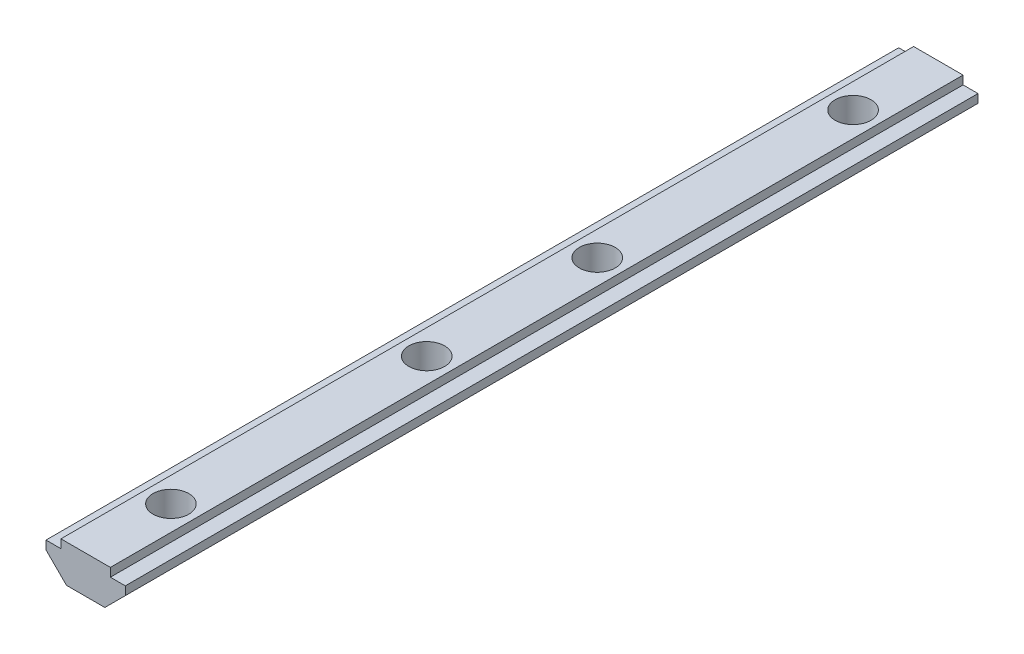
SolidWorks part; units mm, degrees
ref_plane "Front Plane" through (0, 0, 0) normal (0, 0, 1) x (1, 0, 0)
ref_plane "Top Plane" through (0, 0, 0) normal (0, 1, 0) x (1, 0, 0)
ref_plane "Right Plane" through (0, 0, 0) normal (1, 0, 0) x (0, 0, -1)
sketch "Sketch1" plane through (0, 0, 0) normal (0, 0, 1) x (1, 0, 0)
  line L0 (2.25, 0) -> (-2.25, 0)
  line L1 (-2.25, 0) -> (-4.65, 2.4)
  line L2 (-4.65, 2.4) -> (-4.65, 3.4)
  line L3 (-4.65, 3.4) -> (-2.9, 3.4)
  line L4 (-2.9, 3.4) -> (-2.9, 4.4)
  line L5 (-2.9, 4.4) -> (2.9, 4.4)
  line L6 (0, 4.4) -> (0, 0) construction
  line L7 (2.9, 3.4) -> (2.9, 4.4)
  line L8 (4.65, 3.4) -> (2.9, 3.4)
  line L9 (4.65, 2.4) -> (4.65, 3.4)
  line L10 (2.25, 0) -> (4.65, 2.4)
  point P3 (-2.2247, 0)
  dimension "D1" = 5.8
  dimension "D2" = 4.4
  dimension "D3" = 1
  dimension "D4" = 9.3
  dimension "D5" = 45
  dimension "D6" = 1
extrude "Boss-Extrude1" add sketch "Sketch1" along normal blind 100
hole_wizard "M5x0.8 Tapped Hole1" positions "Sketch2" profile "Sketch3" tap size "M5x0.8" standard "ANSI Metric" end condition through all
sketch "Sketch2" plane through (0, 4.4, 0) normal (0, 1, 0) x (1, 0, 0)
  line L0 (2.9, 0) -> (-2.9, 0) construction
  line L1 (4.65, 0) -> (2.9, 0) construction
  line L2 (0, 0) -> (0, -100) construction
  line L3 (2.9, -100) -> (-2.9, -100) construction
  line L5 (-4.65, -50) -> (4.65, -50) construction
  line L6 (-4.65, -100) -> (-4.65, 0) construction
  line L7 (4.65, -100) -> (4.65, 0) construction
  point P0 (0, -10)
  point P2 (0, -40)
  point P27 (0, -60)
  point P28 (0, -90)
  dimension "D1" = 10
  dimension "D2" = 40
sketch "Sketch3" plane through (0, 4.4, 10) normal (1, 0, 0) x (0, 0, 1)
  line L0 (0, 0) -> (0, 4.4)
  line L1 (0, 4.4) -> (2.1, 4.4)
  line L2 (2.1, 4.4) -> (2.1, 0)
  line L5 (2.1, 0) -> (0, 0)
  line L11 (0, -6.35) -> (0, 107.95) construction
  dimension "Thru Tap Drill Dia." = 4.2
  dimension "Thru Tap Drill Depth" = 4.4
